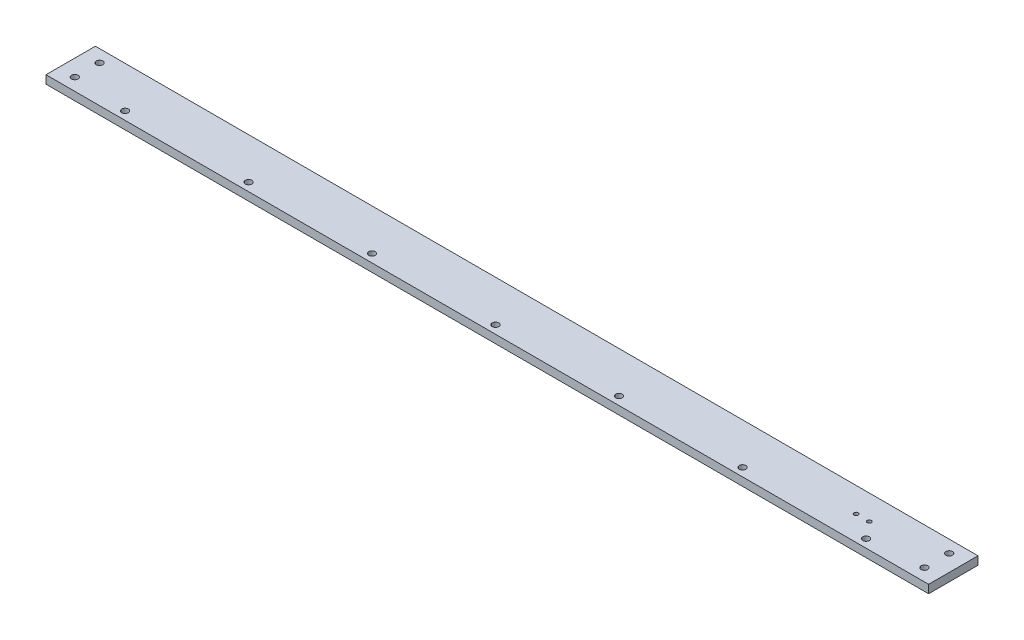
SolidWorks part; units mm, degrees
material "6063-T5"
ref_plane "Front Plane" through (0, 0, 0) normal (0, 0, 1) x (1, 0, 0)
ref_plane "Top Plane" through (0, 0, 0) normal (0, 1, 0) x (1, 0, 0)
ref_plane "Right Plane" through (0, 0, 0) normal (1, 0, 0) x (0, 0, -1)
sketch "Sketch1" plane through (0, 0, 0) normal (0, 1, 0) x (1, 0, 0)
  line L1 (268, -15) -> (-268, -15)
  line L2 (268, -15) -> (268, 15)
  line L3 (268, 15) -> (-268, 15)
  line L4 (-268, -15) -> (-268, 15)
  line L5 (268, -15) -> (-268, 15) construction
  line L6 (268, 15) -> (-268, -15) construction
  point P0 (0, 0)
  dimension "D1" = 30
  dimension "D2" = 536
extrude "Boss-Extrude1" add sketch "Sketch1" along normal blind 5
sketch "Sketch2" plane through (0, 5, 0) normal (0, 1, 0) x (1, 0, 0)
  line L0 (-268, 0) -> (268, 0) construction
  line L1 (-268, 15) -> (-268, -15) construction
  line L2 (268, -15) -> (268, 15) construction
  line L3 (0, 15) -> (0, -15) construction
  line L4 (268, 15) -> (-268, 15) construction
  line L5 (-268, -15) -> (268, -15) construction
  line L6 (-258, 15) -> (-258, -15) construction
  line L7 (-268, -10) -> (268, -10) construction
  point P14 (-258, 7.5)
  point P15 (-258, -7.5)
  point P16 (258, -7.5)
  point P17 (258, 7.5)
  point P20 (0, -10)
  point P21 (-240, -10)
  point P22 (75, -10)
  point P23 (150, -10)
  point P24 (225, -10)
  point P26 (-225, -10)
  point P27 (-150, -10)
  point P28 (-75, -10)
  dimension "D1" = 10
  dimension "D2" = 7.5
  dimension "D3" = 5
  dimension "D4" = 4
hole_wizard "Ø4.0 (4) Diameter Hole1" positions "3DSketch1" profile "Sketch3" hole size "Ø4.0" standard "ISO" end condition through all
sketch3d "3DSketch1"
  point P0 (-258, 5, -7.5)
  point P3 (-258, 5, 7.5)
  point P9 (-225, 5, 10)
  point P12 (-150, 5, 10)
  point P15 (-75, 5, 10)
  point P18 (0, 5, 10)
  point P21 (75, 5, 10)
  point P24 (150, 5, 10)
  point P27 (225, 5, 10)
  point P33 (258, 5, 7.5)
  point P36 (258, 5, -7.5)
sketch "Sketch3" plane through (-258, 5, -7.5) normal (1, 0, 0) x (0, 0, 1)
  line L0 (0, 0) -> (0, 5)
  line L1 (0, 5) -> (2, 5)
  line L2 (2, 5) -> (2, 0)
  line L5 (2, 0) -> (0, 0)
  line L11 (0, -6.35) -> (0, 107.95) construction
  dimension "Thru Hole Dia." = 4
  dimension "Thru Hole Depth" = 5
sketch "Sketch4" plane through (0, 0, 0) normal (0, -1, 0) x (-1, 0, 0)
  line L0 (-268, 0) -> (-196.7257, 0) construction
  line L1 (-268, -15) -> (-268, 15) construction
  point P5 (-216.9805, 0)
  point P6 (-208.9805, 0)
  dimension "D1" = 8
hole_wizard "M3 Tapped Hole1" positions "3DSketch3" profile "Sketch6" tap size "M3" standard "ISO"
sketch3d "3DSketch3"
  point P0 (216.9805, 0, 0)
  point P3 (208.9805, 0, 0)
sketch "Sketch6" plane through (216.9805, 0, 0) normal (1, 0, 0) x (0, 0, -1)
  line L0 (0, 0) -> (0, 8.2511)
  line L1 (0, 8.2511) -> (1.25, 7.5)
  line L2 (1.25, 7.5) -> (1.25, 0)
  line L5 (1.25, 0) -> (0, 0)
  line L10 (0, 8.2511) -> (-1.25, 7.5) construction
  line L11 (0, -6.35) -> (0, 107.95) construction
  dimension "Tap Drill Dia." = 2.5
  dimension "Tap Drill Depth" = 7.5
  dimension "Drill Angle" = 118
